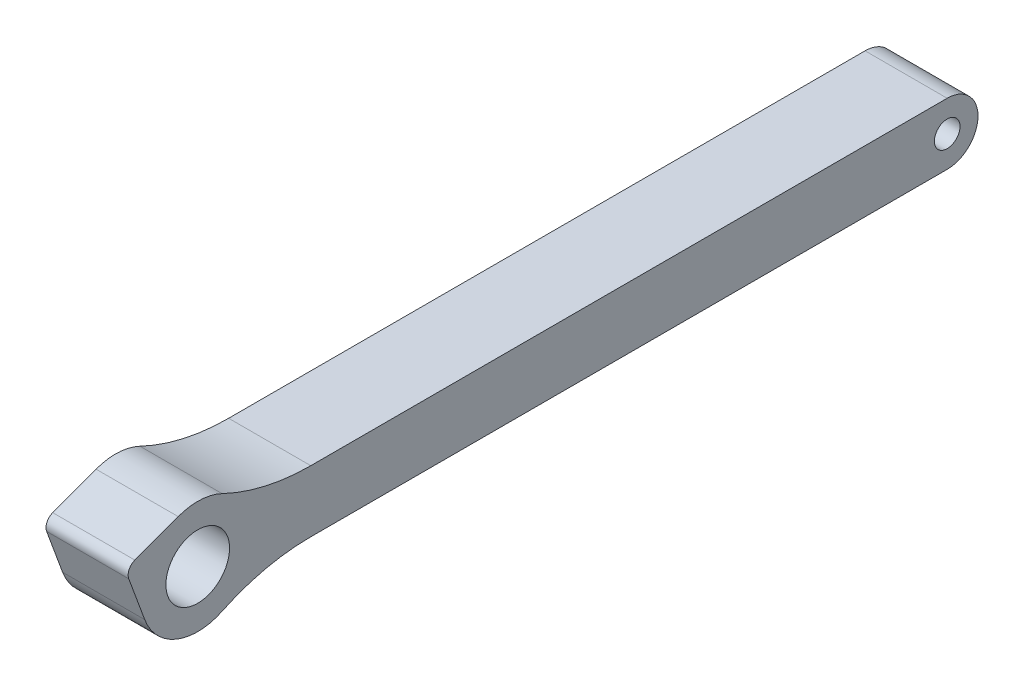
SolidWorks part; units mm, degrees
ref_plane "Front Plane" through (0, 0, 0) normal (0, 0, 1) x (1, 0, 0)
ref_plane "Top Plane" through (0, 0, 0) normal (0, 1, 0) x (1, 0, 0)
ref_plane "Right Plane" through (0, 0, 0) normal (1, 0, 0) x (0, 0, -1)
sketch "Sketch1" plane through (0, 0, 0) normal (1, 0, 0) x (0, 0, -1)
  line L0 (0, 0) -> (-73, 0) construction
  line L2 (-61.9886, 3) -> (0, 3)
  line L3 (-61.9886, -3) -> (0, -3)
  line L5 (-78.1611, -1.9008) -> (-79.7163, 2.322)
  line L6 (-74.9008, 5.1611) -> (-79.1235, 3.606)
  circle A0 centre (0, 0) radius 1.25
  arc A1 (0, -3) -> (0, 3) centre (0, 0) ccw
  arc A2 (-70.625, 4.9608) -> (-74.9008, 5.1611) centre (-73, 0) ccw
  circle A3 centre (-73, 0) radius 3.1
  arc A4 (-70.625, -4.9608) -> (-61.9886, -3) centre (-61.9886, -23) cw
  arc A5 (-70.625, 4.9608) -> (-61.9886, 3) centre (-61.9886, 23) ccw
  arc A6 (-78.1611, -1.9008) -> (-70.625, -4.9608) centre (-73, 0) ccw
  arc A7 (-79.7163, 2.322) -> (-79.1235, 3.606) centre (-78.7779, 2.6676) cw
  point P18 (-80.0619, 3.2604)
  dimension "D1" = 2.5
  dimension "D2" = 6
  dimension "D5" = 6.2
  dimension "D3" = 5.5
  dimension "D6" = 20
  dimension "D7" = 5.5
  dimension "D8" = 5.5
  dimension "D9" = 1
  dimension "D4" = 73
extrude "Boss-Extrude1" add sketch "Sketch1" along normal mid plane 8
sketch "Sketch4" plane through (0, 0, 0) normal (1, 0, 0) x (0, 0, -1)
  point P0 (0, 0)
  point P1 (-73, 0)
